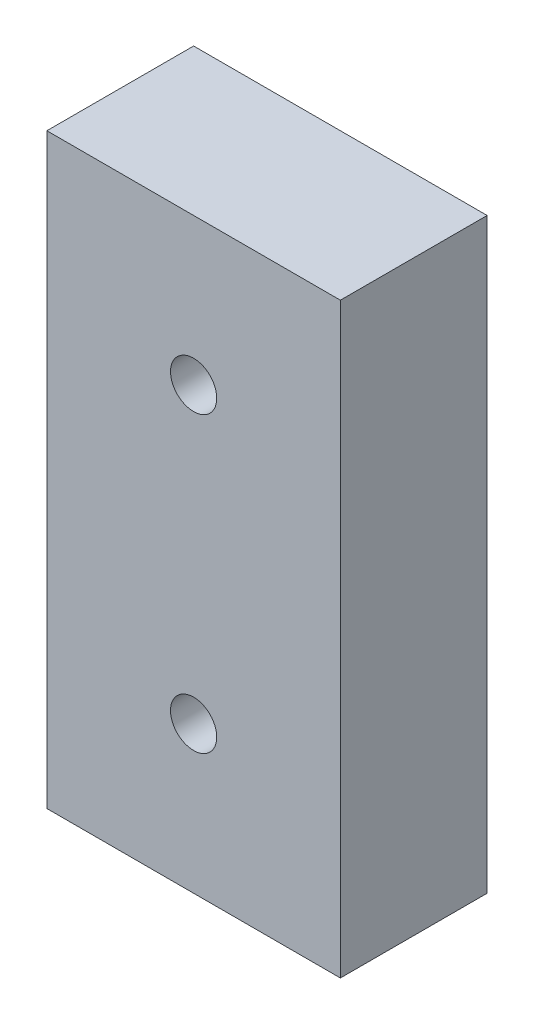
SolidWorks part; units mm, degrees
ref_plane "前视基准面" through (0, 0, 0) normal (0, 0, 1) x (1, 0, 0)
ref_plane "上视基准面" through (0, 0, 0) normal (0, 1, 0) x (1, 0, 0)
ref_plane "右视基准面" through (0, 0, 0) normal (1, 0, 0) x (0, 0, -1)
other "Configuration Table"
sketch "草图1" plane through (0, 0, 0) normal (0, 0, 1) x (1, 0, 0)
  line L1 (0, 0) -> (20, 0)
  line L2 (0, 0) -> (0, -40)
  line L3 (0, -40) -> (20, -40)
  line L4 (20, 0) -> (20, -40)
  dimension "D1" = 20
  dimension "D2" = 40
extrude "凸台-拉伸1" add sketch "草图1" along normal blind 10
sketch "草图2" plane through (0, 0, 10) normal (0, 0, 1) x (1, 0, 0)
  line L0 (0, -20) -> (20, -20) construction
  line L1 (0, 0) -> (0, -40) construction
  line L2 (20, -40) -> (20, 0) construction
  line L3 (20, 0) -> (0, 0) construction
  line L4 (10, -20) -> (10, -10) construction
  circle A0 centre (10, -10) radius 1.575
  circle A1 centre (10, -30) radius 1.575
  dimension "D2" = 3.15
  dimension "D1" = 10
extrude "切除-拉伸1" cut sketch "草图2" against normal through all
